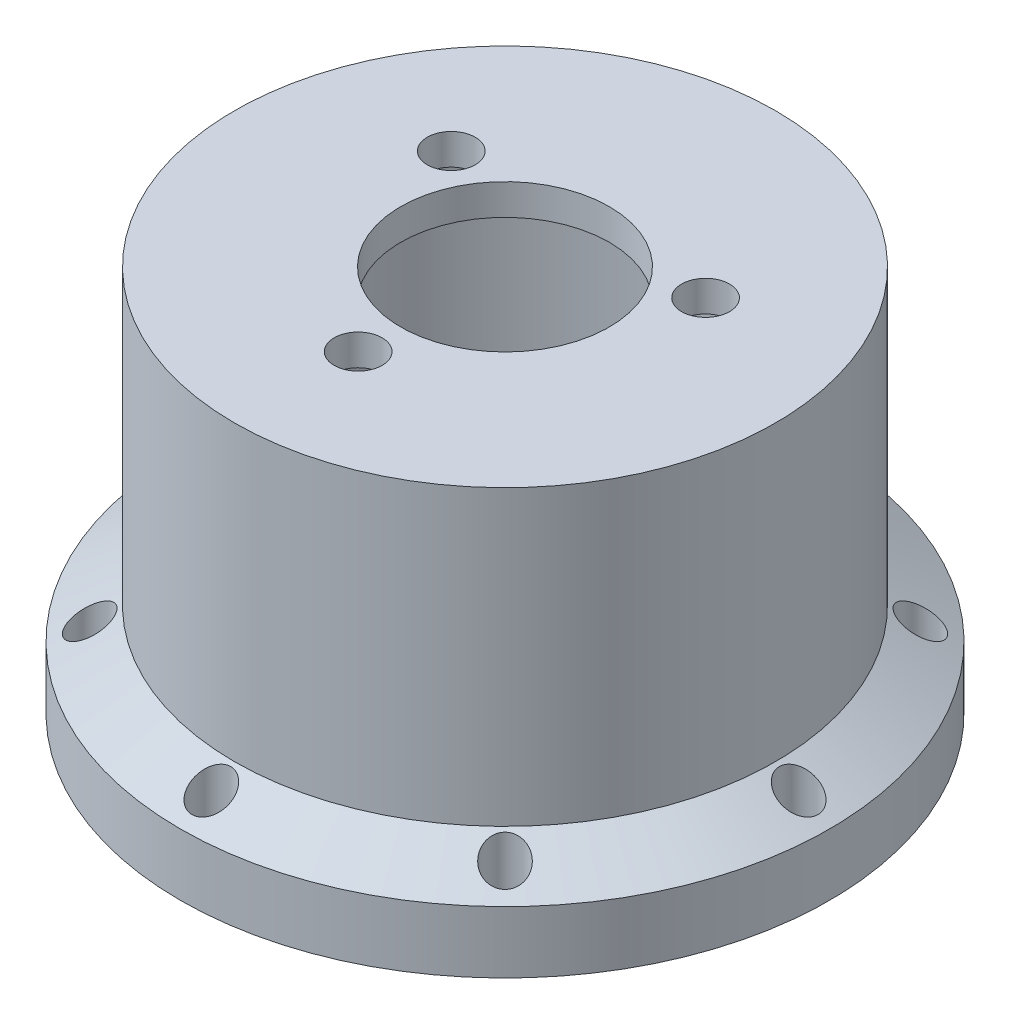
SolidWorks part; units mm, degrees
material "6061 合金"
ref_plane "前视基准面" through (0, 0, 0) normal (0, 0, 1) x (1, 0, 0)
ref_plane "上视基准面" through (0, 0, 0) normal (0, 1, 0) x (1, 0, 0)
ref_plane "右视基准面" through (0, 0, 0) normal (1, 0, 0) x (0, 0, -1)
sketch "草图1" plane through (0, 0, 0) normal (0, 0, 1) x (1, 0, 0)
  line L0 (0, 0) -> (0, 17.6118) construction
  line L1 (-16, 0) -> (-17, 0)
  line L2 (-17, 0) -> (-17, 2)
  line L3 (-17, 2) -> (-21, 2)
  line L4 (-21, 2) -> (-21, 6)
  line L5 (-21, 6) -> (-17.5, 8.0207)
  line L6 (-17.5, 8.0207) -> (-17.5, 27)
  line L7 (-17.5, 27) -> (-6.75, 27)
  line L8 (-6.75, 27) -> (-6.75, 25)
  line L9 (-6.75, 25) -> (-16, 25)
  line L10 (-16, 25) -> (-16, 0)
  dimension "D1" = 2
  dimension "D2" = 4
  dimension "D3" = 34
  dimension "D4" = 32
  dimension "D5" = 4
  dimension "D6" = 25
  dimension "D7" = 2
  dimension "D8" = 13.5
  dimension "D9" = 1.5
  dimension "D10" = 60
revolve "旋转1" add sketch "草图1" angle 360 about L0
sketch "草图2" plane through (0, 2, 0) normal (0, -1, 0) x (1, 0, 0)
  circle A0 centre (0, 0) radius 19 construction
  circle A1 centre (0, -19) radius 1.25
  dimension "D1" = 38
  dimension "D2" = 2.5
extrude "切除-拉伸1" cut sketch "草图2" against normal blind 8
cosmetic thread "装饰螺纹线1" parameters "D2"=3
pattern_circular "阵列(圆周)1" count 8 over 360 about axis through (0, 0, 0) along (0, 1, 0) of "切除-拉伸1"
cosmetic thread "装饰螺纹线2" parameters "D2"=3
cosmetic thread "装饰螺纹线3" parameters "D2"=3
cosmetic thread "装饰螺纹线4" parameters "D2"=3
cosmetic thread "装饰螺纹线5" parameters "D2"=3
cosmetic thread "装饰螺纹线6" parameters "D2"=3
cosmetic thread "装饰螺纹线7" parameters "D2"=3
cosmetic thread "装饰螺纹线8" parameters "D2"=3
sketch "草图3" plane through (0, 27, 0) normal (0, 1, 0) x (1, 0, 0)
  line L0 (0, 0) -> (0, -9.5) construction
  circle A0 centre (0, 0) radius 9.5 construction
  circle A1 centre (0, -9.5) radius 1.55
  circle A2 centre (-8.2272, 4.75) radius 1.55
  circle A3 centre (8.2272, 4.75) radius 1.55
  dimension "D1" = 19
  dimension "D2" = 3.1
  dimension "D5" = 9.5
  dimension "D4" = 9.5
  dimension "D3" = 3
extrude "切除-拉伸2" cut sketch "草图3" against normal through all
